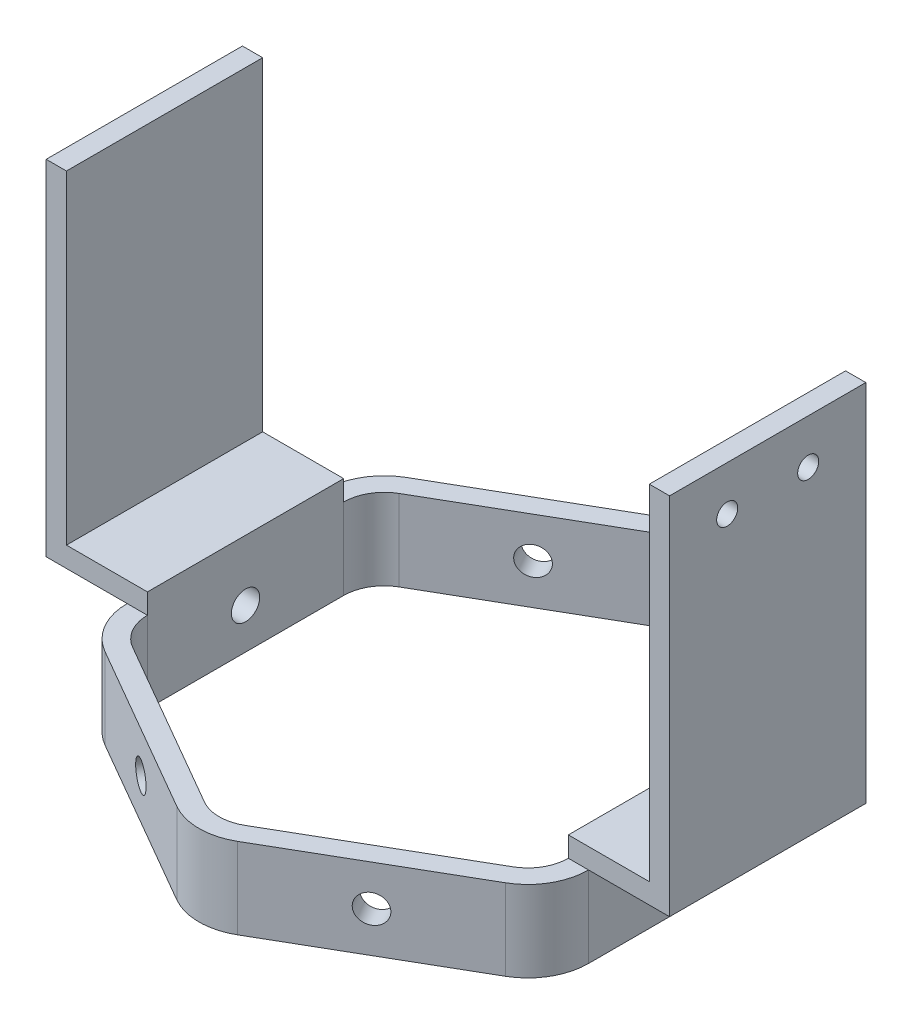
SolidWorks part; units mm, degrees
ref_plane "Front" through (0, 0, 0) normal (0, 0, 1) x (1, 0, 0)
ref_plane "Top" through (0, 0, 0) normal (0, 1, 0) x (1, 0, 0)
ref_plane "Right" through (0, 0, 0) normal (1, 0, 0) x (0, 0, -1)
sketch "Çizim1" plane through (0, 0, 0) normal (0, 1, 0) x (1, 0, 0)
  line L0 (-69.1337, 13.4748) -> (-69.1337, -34.9782)
  line L1 (-74.1337, -34.9782) -> (-74.1337, 13.4748)
  line L2 (34.7893, 13.4748) -> (34.7893, -34.9782)
  line L3 (39.7893, 13.4748) -> (39.7893, -34.9782)
  line L4 (-64.1337, 22.135) -> (-22.1722, 46.3615)
  line L5 (-12.1722, 46.3615) -> (29.7893, 22.135)
  line L6 (32.2893, 26.4652) -> (-9.6722, 50.6916)
  line L7 (-24.6722, 50.6916) -> (-66.6337, 26.4652)
  line L8 (-64.1337, -43.6385) -> (-22.1722, -67.865)
  line L9 (-12.1722, -67.865) -> (29.7893, -43.6385)
  line L10 (-66.6337, -47.9686) -> (-24.6722, -72.1951)
  line L11 (-9.6722, -72.1951) -> (32.2893, -47.9686)
  arc A0 (34.7893, 13.4748) -> (29.7893, 22.135) centre (24.7893, 13.4748) ccw
  arc A1 (29.7893, -43.6385) -> (34.7893, -34.9782) centre (24.7893, -34.9782) ccw
  arc A2 (-12.1722, -67.865) -> (-22.1722, -67.865) centre (-17.1722, -59.2047) cw
  arc A3 (-64.1337, -43.6385) -> (-69.1337, -34.9782) centre (-59.1337, -34.9782) cw
  arc A4 (-69.1337, 13.4748) -> (-64.1337, 22.135) centre (-59.1337, 13.4748) cw
  arc A5 (-12.1722, 46.3615) -> (-22.1722, 46.3615) centre (-17.1722, 37.7013) ccw
  arc A6 (-66.6337, 26.4652) -> (-74.1337, 13.4748) centre (-59.1337, 13.4748) ccw
  arc A7 (-74.1337, -34.9782) -> (-66.6337, -47.9686) centre (-59.1337, -34.9782) ccw
  arc A8 (-24.6722, -72.1951) -> (-9.6722, -72.1951) centre (-17.1722, -59.2047) ccw
  arc A9 (32.2893, -47.9686) -> (39.7893, -34.9782) centre (24.7893, -34.9782) ccw
  arc A10 (39.7893, 13.4748) -> (32.2893, 26.4652) centre (24.7893, 13.4748) ccw
  arc A11 (-9.6722, 50.6916) -> (-24.6722, 50.6916) centre (-17.1722, 37.7013) ccw
  point P15 (34.7893, 19.2483)
  point P18 (34.7893, -40.7517)
  point P21 (-17.1722, -70.7517)
  point P24 (-69.1337, -40.7517)
  point P27 (-69.1337, 19.2483)
  point P30 (-17.1722, 49.2483)
  dimension "D3" = 5
  dimension "D6" = 5
  dimension "D16" = 10
  dimension "D17" = 15
  dimension "D2" = 5
  dimension "D4" = 120
  dimension "D5" = 5
  dimension "D7" = 5
  dimension "D8" = 5
  dimension "D9" = 120
  dimension "D10" = 120
  dimension "D11" = 120
  dimension "D12" = 120
  dimension "D13" = 120
  dimension "D14" = 120
  dimension "D15" = 120
extrude "Yükseklik-Ekstrüzyon1" add sketch "Çizim1" along normal blind 20
sketch "Çizim3" plane through (0, 20, 0) normal (0, 1, 0) x (1, 0, 0)
  line L0 (-94.1337, 13.4748) -> (-69.1337, 13.4748)
  line L1 (-94.1337, -34.9782) -> (-69.1337, -34.9782)
  line L2 (34.7893, 13.4748) -> (59.7893, 13.4748)
  line L3 (34.7893, -34.9782) -> (59.7893, -34.9782)
  line L4 (-94.1337, 13.4748) -> (-94.1337, -34.9782)
  line L5 (-69.1337, 13.4748) -> (-69.1337, -34.9782)
  line L6 (34.7893, 13.4748) -> (34.7893, -34.9782)
  line L7 (59.7893, 13.4748) -> (59.7893, -34.9782)
  line L9 (34.7893, -34.9782) -> (34.7893, 13.4748) construction
  arc A0 (-69.1337, -34.9782) -> (-64.1337, -43.6385) centre (-59.1337, -34.9782) ccw construction
  arc A1 (34.7893, 13.4748) -> (29.7893, 22.135) centre (24.7893, 13.4748) ccw construction
  dimension "D1" = 25
  dimension "D2" = 25
extrude "Yükseklik-Ekstrüzyon2" add sketch "Çizim3" along normal blind 5
sketch "Çizim10" plane through (0, 25, 0) normal (0, 1, 0) x (1, 0, 0)
  line L1 (54.7893, 13.4748) -> (59.7893, 13.4748)
  line L2 (54.7893, 13.4748) -> (54.7893, -34.9782)
  line L3 (54.7893, -34.9782) -> (59.7893, -34.9782)
  line L4 (59.7893, 13.4748) -> (59.7893, -34.9782)
  line L5 (-89.1337, 13.4748) -> (-94.1337, 13.4748)
  line L6 (-89.1337, 13.4748) -> (-89.1337, -34.9782)
  line L7 (-89.1337, -34.9782) -> (-94.1337, -34.9782)
  line L8 (-94.1337, 13.4748) -> (-94.1337, -34.9782)
  point P12 (-94.1337, 13.4748)
  point P14 (-89.9823, 13.4748)
  point P15 (39.7893, 7.1215)
  point P16 (59.7893, 13.4748)
  dimension "D1" = 5
  dimension "D2" = 5
sketch "Çizim12" plane through (39.7893, 0, 0) normal (1, 0, 0) x (0, 0, -1)
  line L0 (-34.9782, 0) -> (13.4748, 0) construction
  line L1 (-34.9782, 0) -> (13.4748, 0) construction
  circle A0 centre (-10.7517, 10) radius 3.5
  point P8 (-10.7517, 0)
  dimension "D1" = 10
  dimension "D2" = 7
extrude "Kes-Ekstrüzyon4" cut sketch "Çizim12" against normal blind 200
sketch "Çizim13" plane through (10.4672, 0, -39.0642) normal (-0.5, 0, 0.866) x (0.866, 0, 0.5)
  line L0 (-68.5857, 0) -> (68.5857, 0) construction
  line L1 (25.198, 0) -> (-23.255, 0) construction
  circle A0 centre (0.9715, 10) radius 3.5
  point P7 (0.9715, 0)
  dimension "D1" = 7
  dimension "D2" = 10
extrude "Kes-Ekstrüzyon5" cut sketch "Çizim13" against normal blind 200 and the other way blind 200 contours A0
sketch "Çizim14" plane through (-28.1182, 0, -48.7021) normal (-0.5, 0, -0.866) x (-0.866, 0, 0.5)
  line L0 (-3.9791, 0) -> (44.4739, 0) construction
  circle A0 centre (20.2474, 10) radius 3.5
  dimension "D2" = 7
  dimension "D1" = 10
extrude "Kes-Ekstrüzyon6" cut sketch "Çizim14" against normal blind 150
extrude "Yükseklik-Ekstrüzyon3" add sketch "Çizim10" along normal blind 80
sketch "Çizim15" plane through (0, 105, 0) normal (0, 1, 0) x (1, 0, 0)
  line L1 (54.7893, 13.4748) -> (59.7893, 13.4748)
  line L2 (54.7893, 13.4748) -> (54.7893, -34.9782)
  line L3 (54.7893, -34.9782) -> (59.7893, -34.9782)
  line L4 (59.7893, 13.4748) -> (59.7893, -34.9782)
extrude "Yükseklik-Ekstrüzyon4" add sketch "Çizim15" along normal blind 5 contours L2 L3 L4 L1
sketch "Çizim11" plane through (54.7893, 0, 0) normal (1, 0, 0) x (0, 0, -1)
  line L1 (13.4748, 110) -> (13.4748, 20) construction
  line L3 (13.4748, 110) -> (-34.9782, 110) construction
  circle A0 centre (-20.7502, 99) radius 2.6
  circle A1 centre (-0.7502, 99) radius 2.6
  point P4 (-0.7502, 19.5)
  point P5 (-20.7502, 46.5504)
  point P6 (-20.7502, 88.2597)
  point P9 (0, 19.5)
  dimension "D1" = 5.2
  dimension "D2" = 5.2
  dimension "D3" = 11
  dimension "D4" = 20
  dimension "D5" = 14.225
extrude "Kes-Ekstrüzyon3" cut sketch "Çizim11" along normal blind 5.5
